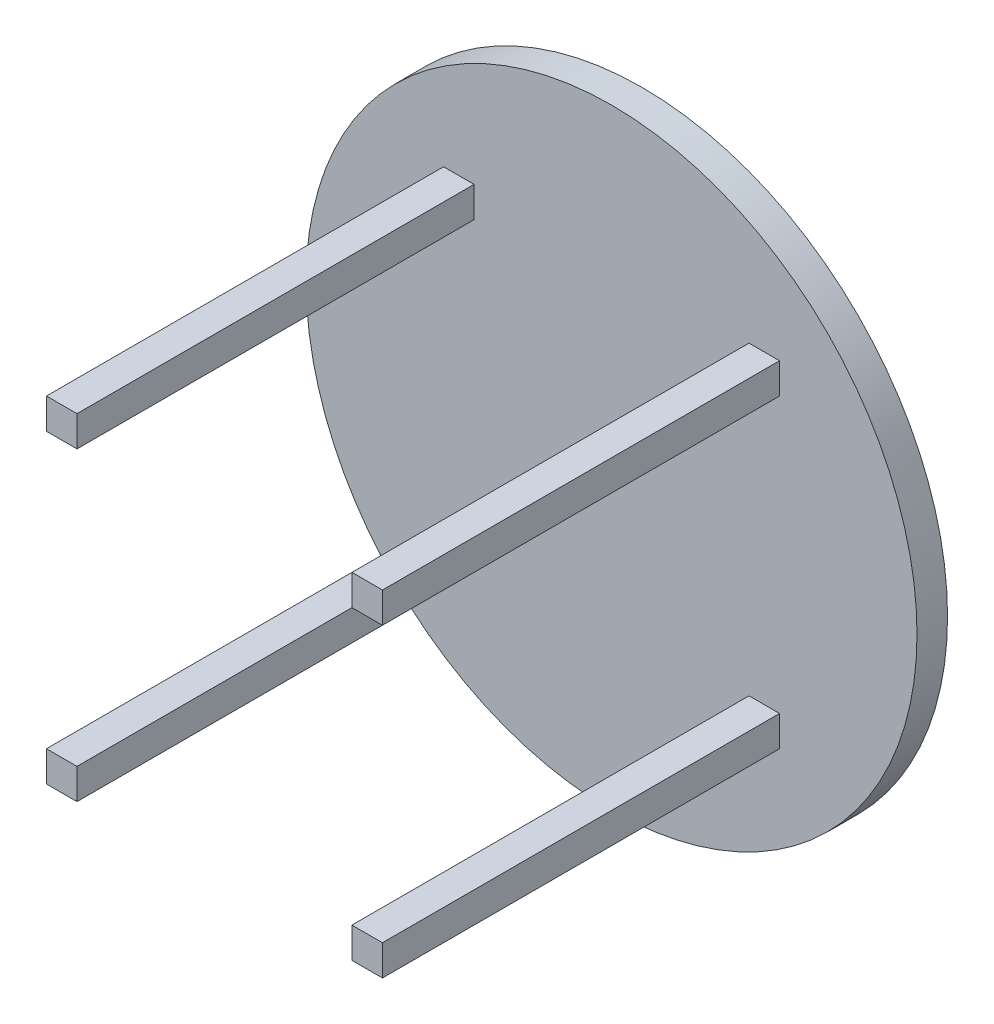
SolidWorks part; units mm, degrees
ref_plane "前视基准面" through (0, 0, 0) normal (0, 0, 1) x (1, 0, 0)
ref_plane "上视基准面" through (0, 0, 0) normal (0, 1, 0) x (1, 0, 0)
ref_plane "右视基准面" through (0, 0, 0) normal (1, 0, 0) x (0, 0, -1)
other "Configuration Table"
sketch "草图1" plane through (0, 0, 0) normal (0, 0, 1) x (1, 0, 0)
  circle A0 centre (0, 0) radius 500
extrude "凸台-拉伸1" add sketch "草图1" along normal blind 50
sketch "草图2" plane through (0, 0, 0) normal (0, 0, 1) x (1, 0, 0)
  line L1 (225, 225) -> (275, 225)
  line L2 (225, 225) -> (225, 275)
  line L3 (225, 275) -> (275, 275)
  line L4 (275, 225) -> (275, 275)
  line L5 (225, 225) -> (275, 275) construction
  line L6 (225, 275) -> (275, 225) construction
  point P0 (250, 250)
extrude "凸台-拉伸2" add sketch "草图2" along normal blind 700
sketch "草图3" plane through (0, 0, 0) normal (0, 0, 1) x (1, 0, 0)
  line L1 (-275, 225) -> (-225, 225)
  line L2 (-275, 225) -> (-275, 275)
  line L3 (-275, 275) -> (-225, 275)
  line L4 (-225, 225) -> (-225, 275)
  line L5 (-275, 225) -> (-225, 275) construction
  line L6 (-275, 275) -> (-225, 225) construction
  point P0 (-250, 250)
extrude "凸台-拉伸3" add sketch "草图3" along normal blind 700
sketch "草图4" plane through (0, 0, 0) normal (0, 0, 1) x (1, 0, 0)
  line L1 (225, -275) -> (275, -275)
  line L2 (225, -275) -> (225, -225)
  line L3 (225, -225) -> (275, -225)
  line L4 (275, -275) -> (275, -225)
  line L5 (225, -275) -> (275, -225) construction
  line L6 (225, -225) -> (275, -275) construction
  point P0 (250, -250)
extrude "凸台-拉伸4" add sketch "草图4" along normal blind 700
sketch "草图5" plane through (0, 0, 0) normal (0, 0, 1) x (1, 0, 0)
  line L1 (-275, -275) -> (-225, -275)
  line L2 (-275, -275) -> (-275, -225)
  line L3 (-275, -225) -> (-225, -225)
  line L4 (-225, -275) -> (-225, -225)
  line L5 (-275, -275) -> (-225, -225) construction
  line L6 (-275, -225) -> (-225, -275) construction
  point P0 (-250, -250)
extrude "凸台-拉伸5" add sketch "草图5" along normal blind 700
sketch "草图6" plane through (0, 275, 0) normal (0, 1, 0) x (1, 0, 0)
  line L1 (-100, -50) -> (100, -50)
  line L2 (-100, -50) -> (-100, 50)
  line L3 (-100, 50) -> (100, 50)
  line L4 (100, -50) -> (100, 50)
  line L5 (-100, -50) -> (100, 50) construction
  line L6 (-100, 50) -> (100, -50) construction
  point P0 (0, 0)
extrude "凸台-拉伸6" add sketch "草图6" along normal blind 50
sketch "草图7" plane through (0, 275, 0) normal (0, 1, 0) x (1, 0, 0)
  line L1 (-75, -25) -> (75, -25)
  line L2 (-75, -25) -> (-75, 25)
  line L3 (-75, 25) -> (75, 25)
  line L4 (75, -25) -> (75, 25)
  line L5 (-75, -25) -> (75, 25) construction
  line L6 (-75, 25) -> (75, -25) construction
  point P0 (0, 0)
extrude "切除-拉伸1" cut sketch "草图7" along normal blind 30
